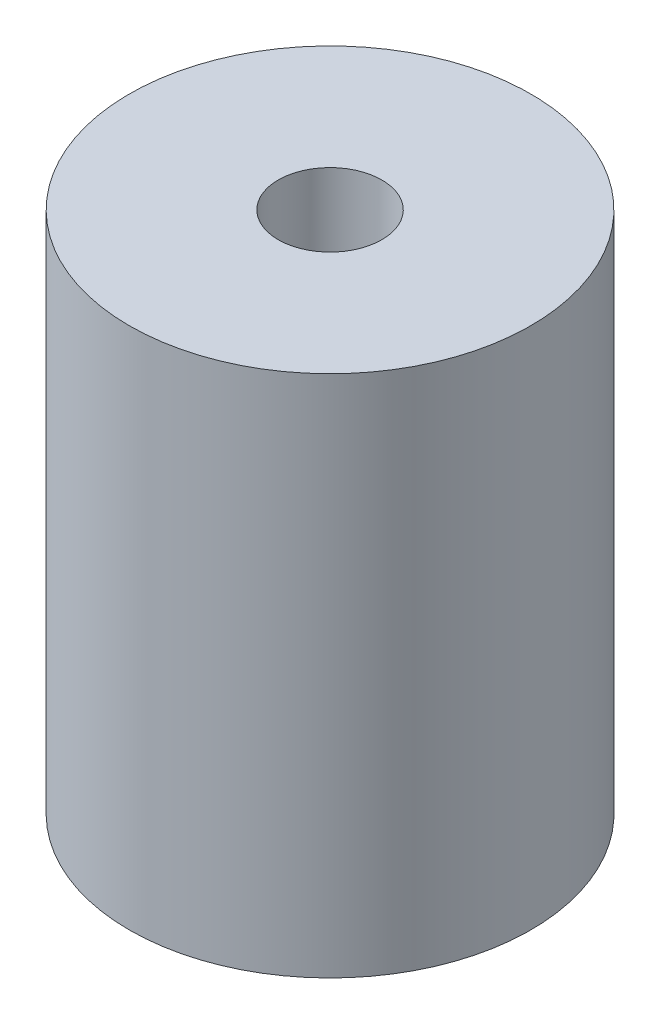
SolidWorks part; units mm, degrees
ref_plane "Front Plane" through (0, 0, 0) normal (0, 0, 1) x (1, 0, 0)
ref_plane "Top Plane" through (0, 0, 0) normal (0, 1, 0) x (1, 0, 0)
ref_plane "Right Plane" through (0, 0, 0) normal (1, 0, 0) x (0, 0, -1)
sketch "Sketch1" plane through (0, 0, 0) normal (0, 1, 0) x (1, 0, 0)
  circle A0 centre (0, 0) radius 9.475
  dimension "D1" = 18.95
extrude "Boss-Extrude1" add sketch "Sketch1" along normal mid plane 24.7
sketch "Sketch2" plane through (0, 12.35, 0) normal (0, 1, 0) x (1, 0, 0)
  circle A0 centre (0, 0) radius 2.445
  dimension "D1" = 4.89
extrude "Cut-Extrude1" cut sketch "Sketch2" against normal blind 10
sketch "Sketch3" plane through (0, -12.35, 0) normal (0, -1, 0) x (1, 0, 0)
  circle A0 centre (0, 0) radius 3.925
  dimension "D1" = 7.85
extrude "Cut-Extrude2" cut sketch "Sketch3" against normal blind 19
